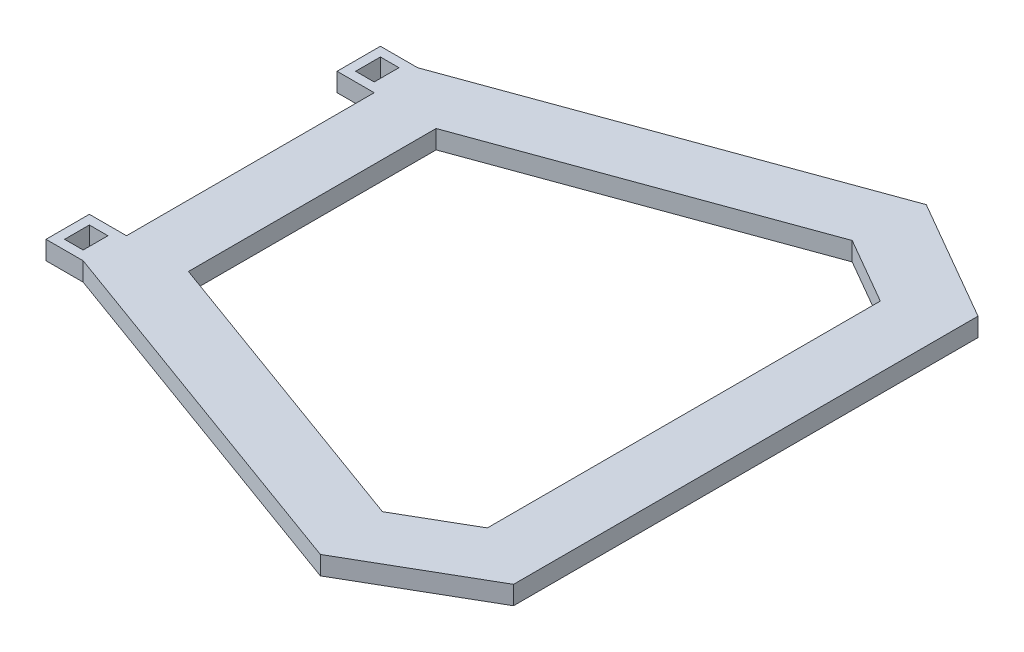
SolidWorks part; units mm, degrees
ref_plane "Front Plane" through (0, 0, 0) normal (0, 0, 1) x (1, 0, 0)
ref_plane "Top Plane" through (0, 0, 0) normal (0, 1, 0) x (1, 0, 0)
ref_plane "Right Plane" through (0, 0, 0) normal (1, 0, 0) x (0, 0, -1)
sketch "Sketch2" plane through (0, 0, 0) normal (0, -1, 0) x (0, 0, -1)
  line L0 (-37.5, 0) -> (37.5, 0)
  line L1 (37.5, 0) -> (48.9189, -19.7782)
  line L2 (48.9189, -19.7782) -> (27, -80)
  line L3 (27, -80) -> (-27, -80)
  line L4 (0, 7.15) -> (0, -7.15) construction
  line L5 (-48.9189, -19.7782) -> (-27, -80)
  line L6 (-37.5, 0) -> (-48.9189, -19.7782)
  line L7 (-31.7265, -10) -> (31.7265, -10)
  line L8 (31.7265, -10) -> (37.9272, -20.7399)
  line L9 (37.9272, -20.7399) -> (19.9979, -70)
  line L10 (19.9979, -70) -> (-19.9979, -70)
  line L11 (-37.9272, -20.7399) -> (-19.9979, -70)
  line L12 (-31.7265, -10) -> (-37.9272, -20.7399)
  point P10 (0, -80)
  point P12 (0, 0)
  dimension "D1" = 75
  dimension "D2" = 80
  dimension "D3" = 60
  dimension "D4" = 110
  dimension "D5" = 54
  dimension "D6" = 10
extrude "Boss-Extrude1" add sketch "Sketch2" along normal blind 3
ref_plane "Plane1" through (-95, 0, 0) normal (-1, 0, 0) x (0, 1, 0)
sketch "Sketch3" plane through (-95, 0, 0) normal (-1, 0, 0) x (0, -1, 0)
  line L0 (13, 27) -> (0, 27)
  line L1 (0, 27) -> (0, -27)
  line L2 (3, 24) -> (3, -24)
  line L3 (0, 48.9189) -> (0, 27) construction
  line L4 (13, 27) -> (13, 24)
  line L5 (13, 24) -> (3, 24)
  line L6 (3, 48.9189) -> (3, 27) construction
  line L7 (3, 27) -> (3, -27) construction
  line L8 (7.15, 0) -> (-7.15, 0) construction
  line L9 (13, -24) -> (3, -24)
  line L10 (13, -27) -> (13, -24)
  line L11 (13, -27) -> (0, -27)
  point P20 (3, 0)
  point P21 (0, 0)
  dimension "D1" = 3
  dimension "D2" = 27
  dimension "D3" = 10
extrude "Boss-Extrude2" add sketch "Sketch3" along normal blind 83 separate body
sketch "Sketch4" plane through (-178, 0, 0) normal (-1, 0, 0) x (0, -1, 0)
  line L0 (13, 27) -> (0, 27) construction
  line L1 (2, 27) -> (1, 27)
  line L2 (2, 27) -> (2, 26)
  line L3 (2, 25) -> (1, 25)
  line L4 (1, 27) -> (1, 25)
  line L5 (7.15, 0) -> (-7.15, 0) construction
  line L6 (3, 27) -> (0, 27) construction
  line L7 (2, 25) -> (4.25, 25)
  line L8 (4.25, 25) -> (4.25, 26)
  line L9 (4.25, 26) -> (2, 26)
  line L10 (13, 24) -> (13, 27) construction
  line L11 (3, -27) -> (0, -27) construction
  line L12 (4.25, -26) -> (2, -26)
  line L13 (4.25, -25) -> (4.25, -26)
  line L14 (2, -25) -> (4.25, -25)
  line L15 (1, -27) -> (1, -25)
  line L16 (2, -25) -> (1, -25)
  line L17 (2, -27) -> (2, -26)
  line L18 (2, -27) -> (1, -27)
  point P8 (1.5, 27)
  point P9 (1.5, 25)
  point P17 (13, 25.5)
  point P18 (4.25, 25.5)
  point P20 (1.5, 27)
  dimension "D1" = 1
  dimension "D2" = 1
  dimension "D3" = 2.25
extrude "Cut-Extrude1" cut sketch "Sketch4" against normal offset from surface (81 mm away) 2 up to face at (-95, -7.25, 0)
delete or keep bodies "Body-Delete/Keep 1" type keep bodies bodies 101
delete or keep bodies "Body-Delete/Keep 2" [suppressed] type keep bodies bodies 103
sketch "Sketch7" [suppressed] plane through (0, 0, 0) normal (0, 1, 0) x (1, 0, 0)
  line L0 (-178, 27) -> (-95, 27) construction
  line L1 (-146.5, 27) -> (-126.5, 27)
  line L2 (-126.5, 27) -> (-126.5, 34)
  line L3 (-126.5, 34) -> (-146.5, 34)
  line L4 (-146.5, 34) -> (-146.5, 27)
  line L5 (-144.5, 29) -> (-128.5, 29)
  line L6 (-128.5, 29) -> (-128.5, 32)
  line L7 (-128.5, 32) -> (-144.5, 32)
  line L8 (-144.5, 32) -> (-144.5, 29)
  line L18 (-7.15, 0) -> (7.15, 0) construction
  line L19 (-95, 27) -> (-89, 27)
  line L20 (-95, 27) -> (-95, 20)
  line L21 (-95, 20) -> (-89, 20)
  line L22 (-89, 27) -> (-89, 20)
  line L31 (-144.5, -32) -> (-144.5, -29)
  line L32 (-128.5, -32) -> (-144.5, -32)
  line L33 (-128.5, -29) -> (-128.5, -32)
  line L34 (-144.5, -29) -> (-128.5, -29)
  line L35 (-146.5, -34) -> (-146.5, -27)
  line L36 (-126.5, -34) -> (-146.5, -34)
  line L37 (-126.5, -27) -> (-126.5, -34)
  line L38 (-146.5, -27) -> (-126.5, -27)
  line L39 (-93.5, 25.5) -> (-90.5, 25.5)
  line L40 (-90.5, 25.5) -> (-90.5, 21.5)
  line L41 (-93.5, 21.5) -> (-90.5, 21.5)
  line L42 (-93.5, 25.5) -> (-93.5, 21.5)
  line L43 (-93.5, -25.5) -> (-93.5, -21.5)
  line L44 (-93.5, -21.5) -> (-90.5, -21.5)
  line L45 (-90.5, -25.5) -> (-90.5, -21.5)
  line L46 (-93.5, -25.5) -> (-90.5, -25.5)
  line L47 (-89, -27) -> (-89, -20)
  line L48 (-95, -20) -> (-89, -20)
  line L49 (-95, -27) -> (-95, -20)
  line L50 (-95, -27) -> (-89, -27)
  point P3 (-136.5, 27)
  point P5 (-136.5, 27)
  point P19 (-136.5, -27)
  dimension "D1" = 20
  dimension "D2" = 7
  dimension "D4" = 6
  dimension "D5" = 7
  dimension "D3" = 2
  dimension "D6" = 1.5
extrude "Boss-Extrude3" [suppressed] add sketch "Sketch7" against normal up to surface (1 mm away)
sketch "Sketch8" plane through (0, 0, 0) normal (0, 1, 0) x (1, 0, 0)
  line L0 (-81.5, 25.5) -> (-84.5, 25.5)
  line L1 (-80, 27) -> (-86, 27)
  line L2 (-80, 27) -> (-80, 20)
  line L3 (-80, 20) -> (-86, 20)
  line L4 (-86, 27) -> (-86, 20)
  line L5 (-84.5, 25.5) -> (-84.5, 21.5)
  line L6 (-81.5, 21.5) -> (-84.5, 21.5)
  line L7 (-81.5, 25.5) -> (-81.5, 21.5)
  line L8 (-1.65, 0) -> (1.65, 0) construction
  line L9 (-81.5, -25.5) -> (-81.5, -21.5)
  line L10 (-81.5, -21.5) -> (-84.5, -21.5)
  line L11 (-84.5, -25.5) -> (-84.5, -21.5)
  line L12 (-86, -27) -> (-86, -20)
  line L13 (-80, -20) -> (-86, -20)
  line L14 (-80, -27) -> (-80, -20)
  line L15 (-80, -27) -> (-86, -27)
  line L16 (-81.5, -25.5) -> (-84.5, -25.5)
  dimension "D1" = 7
  dimension "D2" = 6
  dimension "D3" = 1.5
extrude "Boss-Extrude4" add sketch "Sketch8" against normal up to surface (3 mm away) up to face at (-33.2594, -3, 0)
